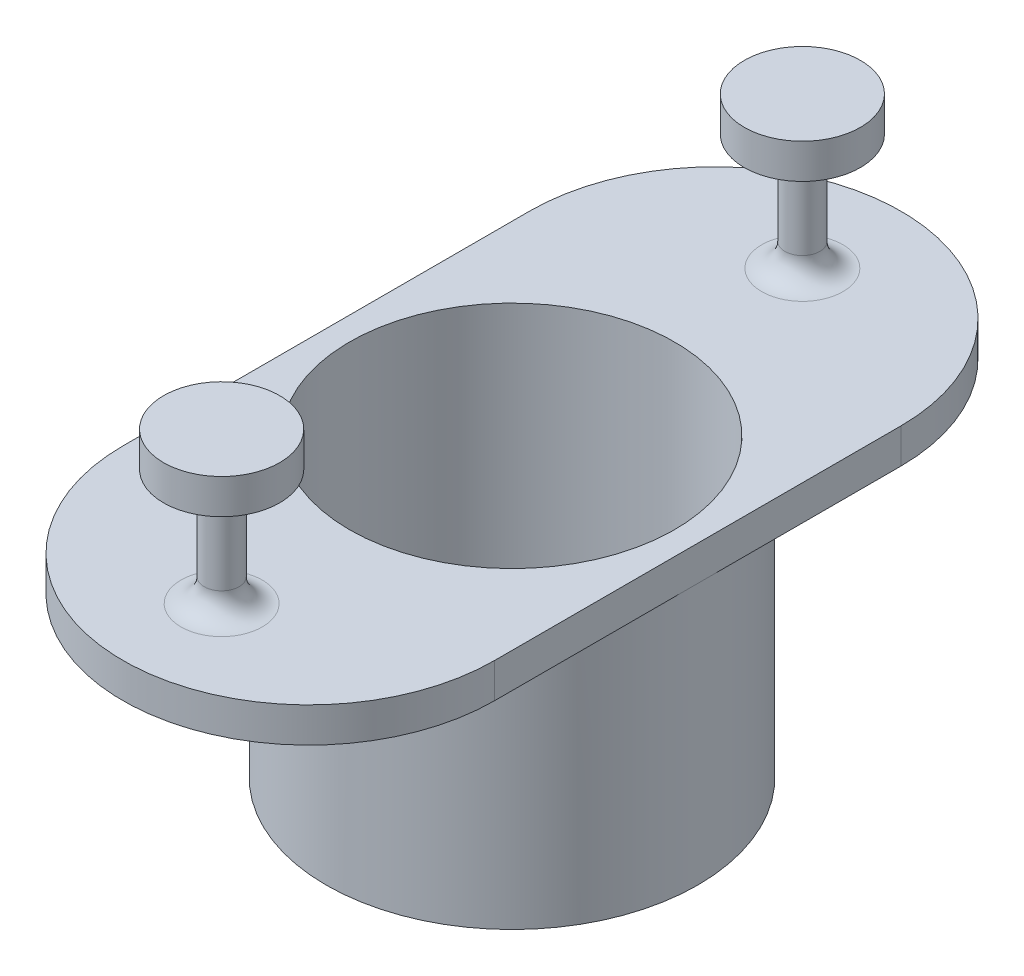
SolidWorks part; units mm, degrees
ref_plane "前视基准面" through (0, 0, 0) normal (0, 0, 1) x (1, 0, 0)
ref_plane "上视基准面" through (0, 0, 0) normal (0, 1, 0) x (1, 0, 0)
ref_plane "右视基准面" through (0, 0, 0) normal (1, 0, 0) x (0, 0, -1)
sketch "Sketch1" plane through (0, 0, 0) normal (0, 1, 0) x (1, 0, 0)
  circle A0 centre (0, 0) radius 16
  dimension "D1" = 32
extrude "Boss-Extrude1" add sketch "Sketch1" along normal blind 22.5
sketch "Sketch2" plane through (0, 22.5, 0) normal (0, 1, 0) x (1, 0, 0)
  line L0 (0, -17.5) -> (0, 17.5) construction
  line L1 (-16, -17.5) -> (-16, 17.5)
  line L2 (16, -17.5) -> (16, 17.5)
  arc A0 (-16, -17.5) -> (16, -17.5) centre (0, -17.5) ccw
  arc A1 (16, 17.5) -> (-16, 17.5) centre (0, 17.5) ccw
  circle A2 centre (0, 0) radius 16 construction
  point P2 (0, 0)
  dimension "D1" = 35
extrude "Boss-Extrude2" add sketch "Sketch2" along normal blind 3
sketch "Sketch3" plane through (0, 25.5, 0) normal (0, 1, 0) x (1, 0, 0)
  line L0 (0, -25) -> (0, 25) construction
  circle A0 centre (0, 25) radius 1.5
  circle A1 centre (0, -25) radius 1.5
  point P12 (0, 0)
  dimension "D1" = 3
  dimension "D2" = 50
extrude "Boss-Extrude3" add sketch "Sketch3" along normal blind 10
sketch "Sketch4" plane through (0, 25.5, 0) normal (0, 1, 0) x (1, 0, 0)
  circle A0 centre (0, 0) radius 14
  circle A1 centre (0, 0) radius 16 construction
  dimension "D1" = 2
extrude "Cut-Extrude1" cut sketch "Sketch4" against normal offset from surface (23.5 mm away) 2 up to face at (0, 0, 16)
sketch "Sketch5" plane through (0, 2, 0) normal (0, 1, 0) x (1, 0, 0)
  circle A0 centre (8, 0) radius 3 construction
  circle A1 centre (8, 0) radius 1.5
  circle A2 centre (-8, 0) radius 1.5
  point P13 (0, 0)
  dimension "D1" = 8
  dimension "D2" = 3
  dimension "D3" = 6
  dimension "D4" = 2
extrude "Cut-Extrude2" cut sketch "Sketch5" against normal through all
sketch "Sketch6" plane through (0, 0, 0) normal (0, -1, 0) x (1, 0, 0)
  circle A0 centre (0, 0) radius 4.3467
sketch "Sketch7" plane through (0, 35.5, 0) normal (0, 1, 0) x (1, 0, 0)
  circle A0 centre (0, 25) radius 5
  circle A1 centre (0, -25) radius 5
  dimension "D1" = 10
extrude "Boss-Extrude4" add sketch "Sketch7" along normal blind 3
fillet "Fillet1" radius 2 4 edges at (0, 35.5, -23.5) (0, 35.5, 26.5) (0, 25.5, 26.5) (0, 25.5, -23.5)
